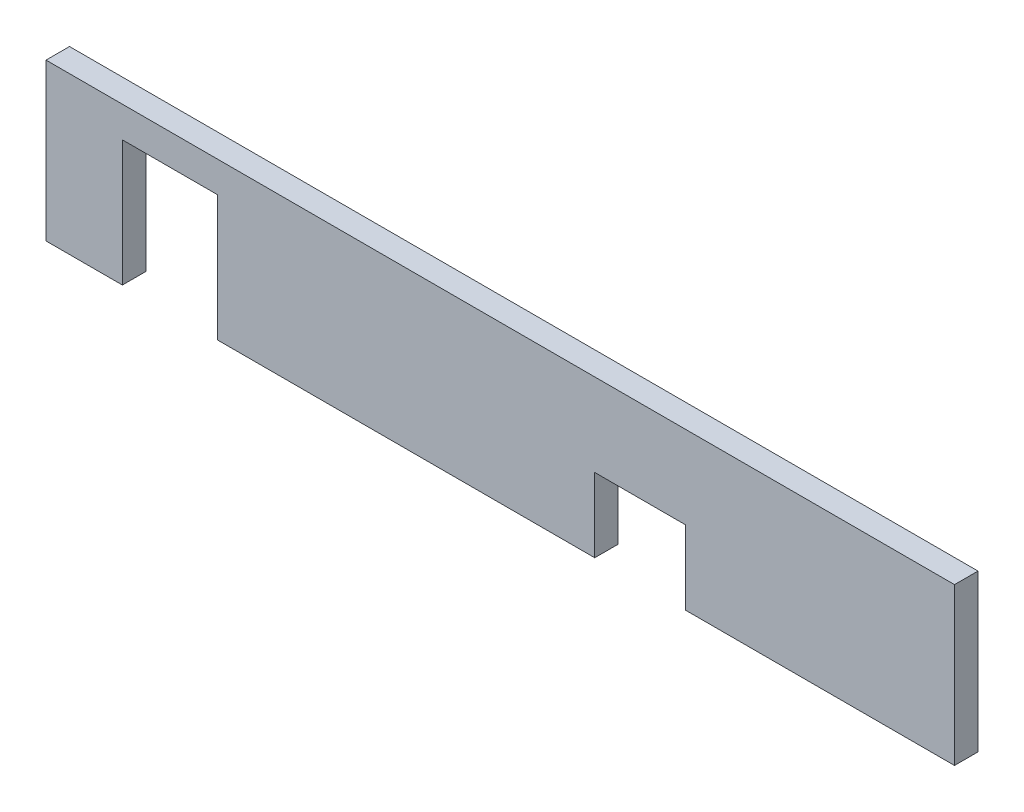
SolidWorks part; units mm, degrees
ref_plane "Front Plane" through (0, 0, 0) normal (0, 0, 1) x (1, 0, 0)
ref_plane "Top Plane" through (0, 0, 0) normal (0, 1, 0) x (1, 0, 0)
ref_plane "Right Plane" through (0, 0, 0) normal (1, 0, 0) x (0, 0, -1)
sketch "Sketch1" plane through (0, 0, 0) normal (0, 0, 1) x (1, 0, 0)
  line L0 (0, 0) -> (9.7532, 0)
  line L2 (0, 0) -> (0, 20)
  line L3 (0, 20) -> (116, 20)
  line L4 (116, 0) -> (116, 20)
  line L5 (9.7532, 0) -> (9.7532, 16.061)
  line L6 (9.7532, 16.061) -> (21.8848, 16.061)
  line L7 (21.8848, 16.061) -> (21.8848, 0)
  line L8 (21.8848, 0) -> (70.0647, 0)
  line L9 (70.0647, 0) -> (70.0647, 9.4366)
  line L10 (70.0647, 9.4366) -> (81.6216, 9.4366)
  line L11 (81.6216, 9.4366) -> (81.6216, 0)
  line L12 (81.6216, 0) -> (116, 0)
  point P5 (0, 0)
  point P14 (0, 0)
  dimension "D1" = 116
extrude "Boss-Extrude1" add sketch "Sketch1" along normal blind 3
